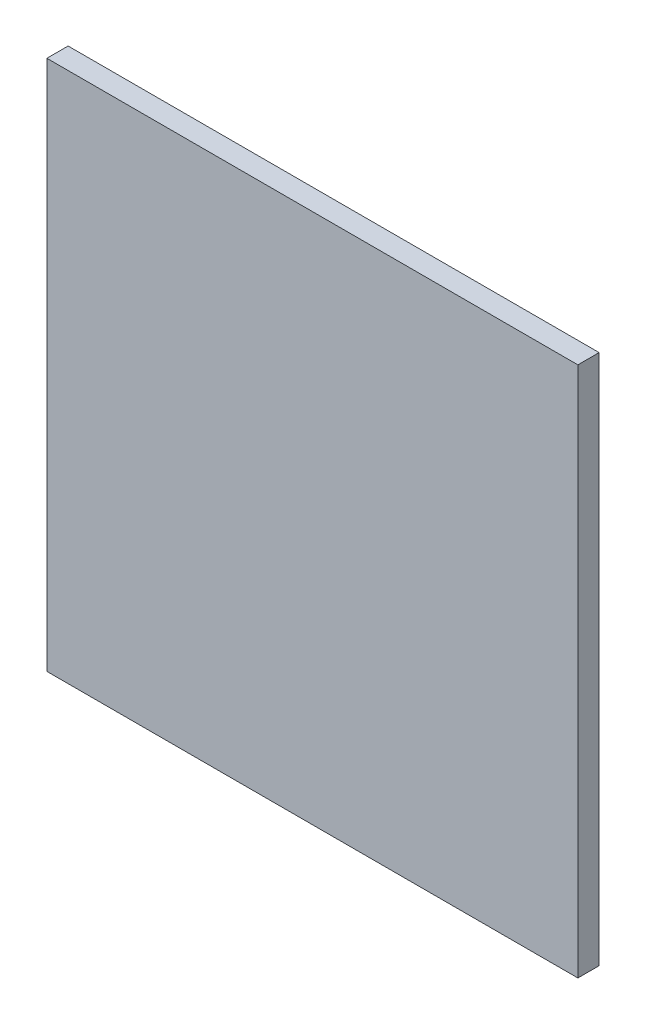
SolidWorks part; units mm, degrees
ref_plane "Front Plane" through (0, 0, 0) normal (0, 0, 1) x (1, 0, 0)
ref_plane "Top Plane" through (0, 0, 0) normal (0, 1, 0) x (1, 0, 0)
ref_plane "Right Plane" through (0, 0, 0) normal (1, 0, 0) x (0, 0, -1)
sketch "Sketch1" plane through (0, 0, 0) normal (0, 0, 1) x (1, 0, 0)
  line L1 (-125, -125) -> (125, -125)
  line L2 (-125, -125) -> (-125, 125)
  line L3 (-125, 125) -> (125, 125)
  line L4 (125, -125) -> (125, 125)
  line L5 (-125, -125) -> (125, 125) construction
  line L6 (-125, 125) -> (125, -125) construction
  point P0 (0, 0)
  dimension "D1" = 250
  dimension "D2" = 250
extrude "Boss-Extrude1" add sketch "Sketch1" along normal blind 10
